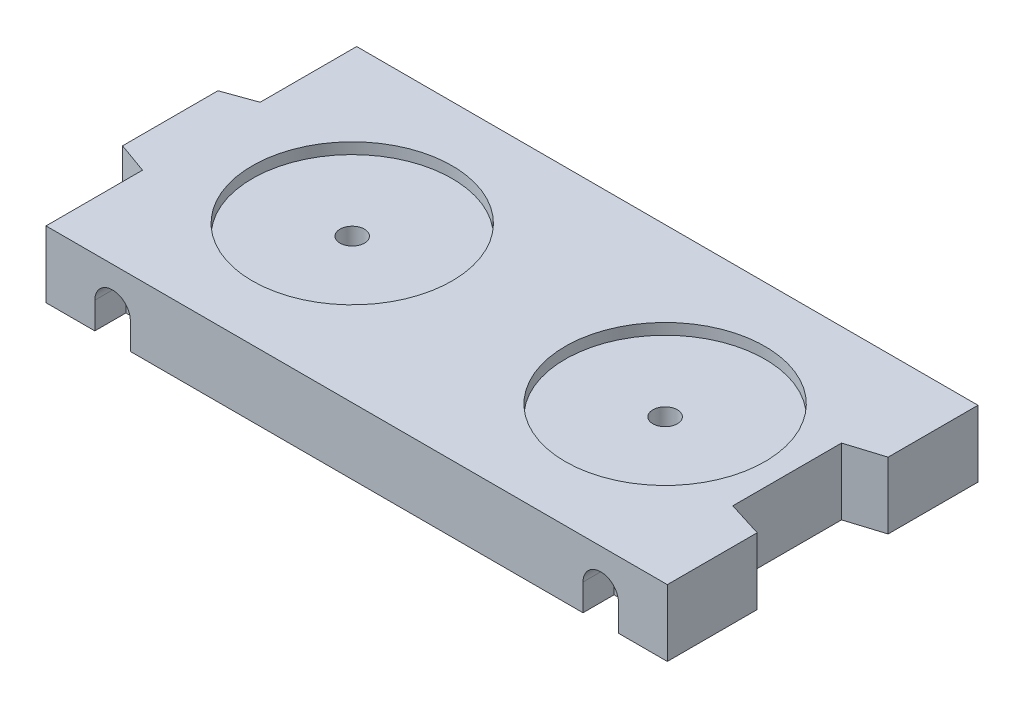
SolidWorks part; units mm, degrees
material "Carburized and nitrided special steel"
ref_plane "Piano frontale" through (0, 0, 0) normal (0, 0, 1) x (1, 0, 0)
ref_plane "Piano superiore" through (0, 0, 0) normal (0, 1, 0) x (1, 0, 0)
ref_plane "Piano destro" through (0, 0, 0) normal (1, 0, 0) x (0, 0, -1)
sketch "Schizzo1" plane through (0, 0, 0) normal (0, 1, 0) x (1, 0, 0)
  line L0 (-14, 91.5) -> (-14, 48.5)
  line L1 (0, 0) -> (280, 0)
  line L2 (0, 0) -> (0, 43.5)
  line L3 (0, 140) -> (280, 140)
  line L4 (280, 0) -> (280, 40.5)
  line L5 (264, 94.5) -> (264, 45.5)
  line L6 (0, 70) -> (193.0838, 70) construction
  line L7 (-14, 91.5) -> (0, 96.5)
  line L8 (264, 94.5) -> (280, 99.5)
  line L9 (264, 45.5) -> (280, 40.5)
  line L10 (-14, 48.5) -> (0, 43.5)
  line L11 (0, 96.5) -> (0, 140)
  line L12 (280, 99.5) -> (280, 140)
  point P15 (264, 70)
  point P17 (-14, 70)
  dimension "D1" = 280
  dimension "D2" = 140
  dimension "D3" = 14
  dimension "D4" = 16
  dimension "D5" = 21.5
  dimension "D6" = 24.5
  dimension "D7" = 70
  dimension "D8" = 26.5
  dimension "D9" = 40.5
extrude "Estrusione1" add sketch "Schizzo1" along normal blind 30
sketch "Schizzo2" plane through (0, 0, 0) normal (0, 0, 1) x (1, 0, 0)
  line L0 (0, 0) -> (280, 0) construction
  line L1 (0, 30) -> (0, 0) construction
  line L2 (22, 12) -> (22, 0)
  line L3 (22, 0) -> (38, 0)
  line L4 (38, 0) -> (38, 12)
  arc A0 (38, 12) -> (22, 12) centre (30, 12) ccw
  dimension "D1" = 12
  dimension "D2" = 30
extrude "Estrusione2" cut sketch "Schizzo2" against normal blind 14
pattern_linear "Ripetizione a L1" count 2 spacing 220 along (1, 0, 0) count 2 spacing 126 along (0, 0, -1) of "Estrusione2"
sketch "Schizzo3" plane through (0, 30, 0) normal (0, 1, 0) x (1, 0, 0)
  line L0 (-14, 70) -> (279.0716, 70) construction
  line L1 (-14, 91.5) -> (-14, 48.5) construction
  line L2 (280, 140) -> (0, 140) construction
  line L3 (0, 140) -> (0, 96.5) construction
  line L4 (280, 99.5) -> (280, 140) construction
  circle A0 centre (68, 70) radius 45
  circle A1 centre (209, 70) radius 45
  dimension "D5" = 90
  dimension "D6" = 90
  dimension "D1" = 70
  dimension "D2" = 68
  dimension "D3" = 141
  dimension "D4" = 71
extrude "Estrusione3" cut sketch "Schizzo3" against normal blind 5
hole_wizard "M10 Lamatura per vite a copertura cilindrica esagonale2" positions "Schizzo8" profile "Schizzo7" counterbore size "M10" standard "ISO" end condition through all
sketch "Schizzo8" plane through (0, 0, 0) normal (0, -1, 0) x (1, 0, 0)
  line L0 (38, 0) -> (242, 0) construction
  line L1 (0, -43.5) -> (0, 0) construction
  line L2 (280, 0) -> (280, -40.5) construction
  point P0 (68, -70)
  point P1 (209, -70)
  dimension "D1" = 70
  dimension "D2" = 70
  dimension "D3" = 68
  dimension "D4" = 71
sketch "Schizzo7" plane through (68, 0, -70) normal (1, 0, 0) x (0, 0, -1)
  line L0 (0, 0) -> (0, 30)
  line L1 (0, 30) -> (5.5, 30)
  line L3 (5.5, 30) -> (5.5, 10)
  line L4 (5.5, 10) -> (9, 10)
  line L5 (9, 10) -> (9, 0)
  line L7 (9, 0) -> (0, 0)
  line L11 (0, -6.35) -> (0, 107.95) construction
  dimension "Thru Hole Dia." = 11
  dimension "Thru Hole Depth" = 30
  dimension "C'Bore Dia." = 18
  dimension "C'Bore Depth" = 10
hole_wizard "M10 Tapped Hole1" positions "Schizzo10" profile "Schizzo9" tap size "M10" standard "ISO"
sketch "Schizzo10" plane through (0, 0, 0) normal (0, -1, 0) x (1, 0, 0)
  line L0 (-18.3355, -70) -> (296.3937, -70) construction
  line L1 (138.5, 15.0115) -> (138.5, -153.9456) construction
  line L2 (280, 0) -> (280, -40.5) construction
  point P0 (93.5, -25)
  point P1 (183.5, -25)
  point P3 (93.5, -115)
  point P5 (183.5, -115)
  dimension "D1" = 141.5
  dimension "D2" = 45
  dimension "D3" = 45
  dimension "D4" = 45
  dimension "D5" = 45
  dimension "D6" = 45
  dimension "D7" = 45
  dimension "D8" = 45
  dimension "D9" = 45
sketch "Schizzo9" plane through (93.5, 0, -25) normal (1, 0, 0) x (0, 0, -1)
  line L0 (0, 0) -> (0, 27.5537)
  line L1 (0, 27.5537) -> (4.25, 25)
  line L2 (4.25, 25) -> (4.25, 0)
  line L5 (4.25, 0) -> (0, 0)
  line L10 (0, 27.5537) -> (-4.25, 25) construction
  line L11 (0, -6.35) -> (0, 107.95) construction
  dimension "Tap Drill Dia." = 8.5
  dimension "Tap Drill Depth" = 25
  dimension "Drill Angle" = 118
cosmetic thread "Filettatura del foro1" parameters "D1"=20, "D2"=10
cosmetic thread "Filettatura del foro2" parameters "D1"=20, "D2"=10
cosmetic thread "Filettatura del foro3" parameters "D1"=20, "D2"=10
cosmetic thread "Filettatura del foro4" parameters "D1"=20, "D2"=10
chamfer "Smusso1" [suppressed] distance 4 angle 45
ref_plane "Piano1" through (0, 0, -70) normal (0, 0, 1) x (1, 0, 0)
ref_plane "Piano2" through (140, 0, 0) normal (-1, 0, 0) x (0, 0, 1)
